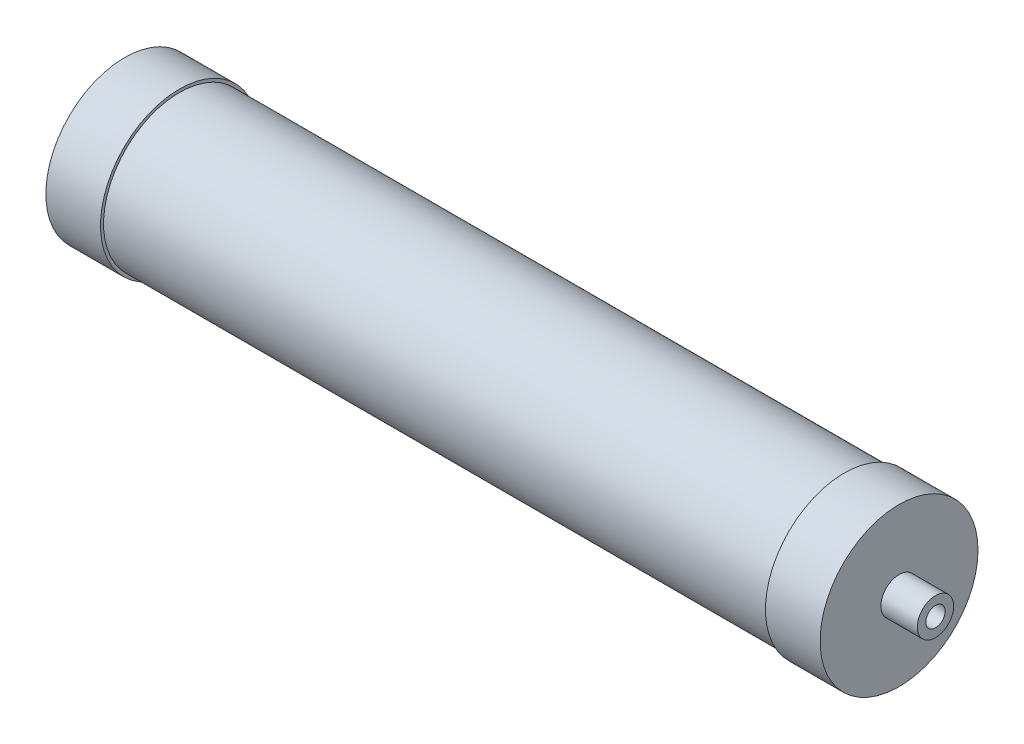
SolidWorks part; units mm, degrees
ref_plane "Front Plane" through (0, 0, 0) normal (0, 0, 1) x (1, 0, 0)
ref_plane "Top Plane" through (0, 0, 0) normal (0, 1, 0) x (1, 0, 0)
ref_plane "Right Plane" through (0, 0, 0) normal (1, 0, 0) x (0, 0, -1)
other "Configuration Table"
sketch "Sketch1" plane through (0, 0, 0) normal (1, 0, 0) x (0, 0, -1)
  circle A0 centre (0, 0) radius 25
  dimension "D1" = 50
extrude "Body" add sketch "Sketch1" along normal blind 255 from offset 127.5
sketch "Sketch2" plane through (0, 0, 0) normal (1, 0, 0) x (0, 0, -1)
  circle A0 centre (0, 0) radius 26
  dimension "D1" = 52
extrude "End_Cap_In" add sketch "Sketch2" along normal blind 18 from offset 127.5
sketch "Sketch3" plane through (0, 0, 0) normal (1, 0, 0) x (0, 0, -1)
  circle A0 centre (0, 0) radius 26
  dimension "D1" = 52
extrude "End_Cap_Out" add sketch "Sketch3" along normal blind 18 from offset 109.5
sketch "Sketch4" plane through (0, 0, 0) normal (1, 0, 0) x (0, 0, -1)
  circle A0 centre (0, 0) radius 6
  dimension "D1" = 12
extrude "Inlet_Port" add sketch "Sketch4" along normal blind 12 from offset 139.5
sketch "Sketch5" plane through (0, 0, 0) normal (1, 0, 0) x (0, 0, -1)
  circle A0 centre (0, 0) radius 3.2
  dimension "D1" = 6.4
extrude "Inlet_Socket" cut sketch "Sketch5" along normal blind 10 from offset 139.5
sketch "Sketch6" plane through (0, 0, 0) normal (1, 0, 0) x (0, 0, -1)
  circle A0 centre (0, 0) radius 6
  dimension "D1" = 12
extrude "Outlet_Port" add sketch "Sketch6" along normal blind 12 from offset 127.5
sketch "Sketch7" plane through (0, 0, 0) normal (1, 0, 0) x (0, 0, -1)
  circle A0 centre (0, 0) radius 3.2
  dimension "D1" = 6.4
extrude "Outlet_Socket" cut sketch "Sketch7" against normal blind 10 from offset 139.5
equation "\"Jar_OD\"= 90  'ASSUMED - Part G fallback - jar outer diameter"
equation "\"Jar_H\"= 120  'ASSUMED - Part G fallback - jar height"
equation "\"Pump_L\"= 45  'ASSUMED - Part G fallback"
equation "\"Pump_W\"= 24  'ASSUMED - Part G fallback"
equation "\"Pump_H\"= 33  'ASSUMED - Part G fallback"
equation "\"Pump_Outlet_OD\"= 7.5  'ASSUMED - Part G fallback"
equation "\"Tube_OD\"= 8  'ASSUMED - Part G fallback"
equation "\"Tube_ID\"= 6  'ASSUMED - Part G fallback"
equation "\"TDS_Body_Dia\"= 12  'ASSUMED - Part G fallback"
equation "\"TDS_Wet_Len\"= 45  'ASSUMED - Part G fallback - length in water"
equation "\"DS_Tube_Dia\"= 6  'ASSUMED - Part G fallback"
equation "\"DS_Tube_Len\"= 50  'ASSUMED - Part G fallback"
equation "\"ORP_Body_Dia\"= 12  'ASSUMED - Part G fallback"
equation "\"ORP_Body_Len\"= 150  'ASSUMED - Part G fallback"
equation "\"ORP_Cap_Dia\"= 16  'ASSUMED - Part G fallback"
equation "\"Turb_W\"= 33  'ASSUMED - Part G fallback - head width"
equation "\"Turb_D\"= 28  'ASSUMED - Part G fallback - head depth"
equation "\"Turb_H\"= 30  'ASSUMED - Part G fallback - head height"
equation "\"Turb_Slot_W\"= 10  'ASSUMED - Part G fallback - slot width"
equation "\"Flow_L\"= 62  'ASSUMED - Part G fallback YF-S201"
equation "\"Flow_W\"= 36  'ASSUMED - Part G fallback"
equation "\"Flow_H\"= 35  'ASSUMED - Part G fallback"
equation "\"Thread_G12_OD\"= 20.955  'ASSUMED - Part G fallback thread G1/2 (major diameter)"
equation "\"Valve_L\"= 75  'ASSUMED - Part G fallback"
equation "\"Valve_W\"= 45  'ASSUMED - Part G fallback"
equation "\"Valve_H\"= 60  'ASSUMED - Part G fallback"
equation "\"Tee_L\"= 40  'ASSUMED - Part G fallback - overall length"
equation "\"Tee_Branch_L\"= 25  'ASSUMED - Part G fallback"
equation "\"Tee_OD\"= 12  'ASSUMED - Part G fallback"
equation "\"LED_Board_L\"= 20  'ASSUMED - Part G fallback"
equation "\"LED_Board_W\"= 20  'ASSUMED - Part G fallback - LED at centre"
equation "\"GUVA_L\"= 20  'ASSUMED - Part G fallback"
equation "\"GUVA_W\"= 12  'ASSUMED - Part G fallback - sensor at centre"
equation "\"Reed_L\"= 27  'ASSUMED - Part G fallback MC-38 half"
equation "\"Reed_W\"= 14  'ASSUMED - Part G fallback"
equation "\"Reed_H\"= 8  'ASSUMED - Part G fallback"
equation "\"ESP_L\"= 51  'ASSUMED - Part G fallback"
equation "\"ESP_W\"= 28  'ASSUMED - Part G fallback"
equation "\"TFT_L\"= 58  'ASSUMED - Part G fallback - board"
equation "\"TFT_W\"= 35  'ASSUMED - Part G fallback - board"
equation "\"TFT_Win_L\"= 35  'ASSUMED - Part G fallback - visible window"
equation "\"TFT_Win_W\"= 28  'ASSUMED - Part G fallback - visible window"
equation "\"Relay_L\"= 50  'ASSUMED - Part G fallback"
equation "\"Relay_W\"= 26  'ASSUMED - Part G fallback"
equation "\"Relay_H\"= 19  'ASSUMED - Part G fallback"
equation "\"Mosfet_L\"= 34  'ASSUMED - Part G fallback"
equation "\"Mosfet_W\"= 17  'ASSUMED - Part G fallback"
equation "\"Mosfet_H\"= 12  'ASSUMED - Part G fallback"
equation "\"TDS_Board_L\"= 42  'ASSUMED - Part G fallback"
equation "\"TDS_Board_W\"= 32  'ASSUMED - Part G fallback"
equation "\"Turb_Board_L\"= 38  'ASSUMED - Part G fallback"
equation "\"Turb_Board_W\"= 28  'ASSUMED - Part G fallback"
equation "\"BNC_Thread_Dia\"= 9.5  'ASSUMED - Part G fallback"
equation "\"Plate_L\"= 420  'ASSUMED - Part G fallback"
equation "\"Plate_W\"= 297  'ASSUMED - Part G fallback"
equation "\"Plate_T\"= 6  'ASSUMED - Part G fallback"
equation "\"Booster_L\"= 150  'ASSUMED - Part G fallback - booster pump"
equation "\"Booster_W\"= 95  'ASSUMED - Part G fallback"
equation "\"Booster_H\"= 100  'ASSUMED - Part G fallback"
equation "\"PTube_OD\"= 6.35  'ASSUMED - Part G fallback - product tube 1/4 inch"
equation "\"Qz_Out\"= 12  'ASSUMED - Part G fallback - quartz channel outside square"
equation "\"Qz_Path\"= 10  'ASSUMED - Part G fallback - quartz channel inside light path"
equation "\"Qz_L\"= 40  'ASSUMED - Part G fallback - quartz channel length"
equation "\"LED860_Dia\"= 5  'ASSUMED - Part G fallback - 860 nm LED"
equation "\"BPW_L\"= 5.4  'ASSUMED - Part G fallback - BPW34"
equation "\"BPW_W\"= 4.3  'ASSUMED - Part G fallback - BPW34"
equation "\"Cart_Dia\"= 50  'ASSUMED - Part G fallback - sediment and pre-carbon cartridges"
equation "\"Cart_L\"= 255  'ASSUMED - Part G fallback"
equation "\"UF_Dia\"= 50  'ASSUMED - Part G fallback - UF cartridge"
equation "\"UF_L\"= 260  'ASSUMED - Part G fallback"
equation "\"RO_Dia\"= 62  'ASSUMED - Part G fallback - RO membrane housing"
equation "\"RO_L\"= 300  'ASSUMED - Part G fallback"
equation "\"UVC_Dia\"= 40  'ASSUMED - Part G fallback - UV-C chamber"
equation "\"UVC_L\"= 300  'ASSUMED - Part G fallback"
equation "\"Tank_W\"= 260  'ASSUMED - Part G fallback - storage tank"
equation "\"Tank_D\"= 160  'ASSUMED - Part G fallback"
equation "\"Tank_H\"= 300  'ASSUMED - Part G fallback"
equation "\"Cab_W\"= 400  'ASSUMED - Part G fallback - purifier cabinet"
equation "\"Cab_D\"= 270  'ASSUMED - Part G fallback"
equation "\"Cab_H\"= 560  'ASSUMED - Part G fallback"
equation "\"ORP_Board_L\"= 40  'ASSUMED - Part G fallback - ORP buffer board"
equation "\"ORP_Board_W\"= 30  'ASSUMED - Part G fallback"
equation "\"Opt_Board_L\"= 50  'ASSUMED - Part G fallback - optical front-end board"
equation "\"Opt_Board_W\"= 40  'ASSUMED - Part G fallback"
equation "\"Buck_L\"= 43  'ASSUMED - Part G fallback - 12 V to 5 V buck module"
equation "\"Buck_W\"= 21  'ASSUMED - Part G fallback"
equation "\"Buck_H\"= 14  'ASSUMED - Part G fallback"
equation "\"BB_L\"= 165  'ASSUMED - Part G fallback - breadboard (As_Built_R3 only)"
equation "\"BB_W\"= 55  'ASSUMED - Part G fallback"
equation "\"BB_H\"= 10  'ASSUMED - Part G fallback"
equation "\"Cuv_W\"= 12.5  'ASSUMED - old R3 cuvette (station suppressed in SS4)"
equation "\"Cuv_D\"= 12.5  'ASSUMED - old R3 cuvette (station suppressed in SS4)"
equation "\"Cuv_H\"= 45  'ASSUMED - old R3 cuvette (station suppressed in SS4)"
equation "\"Probe_Clr\"= 0.3  'DESIGN VALUE - Part C rule 3 - printed probe hole = diameter + 0.3"
equation "\"Label_H\"= 0.6  'DESIGN VALUE - Part D - raised label height"
